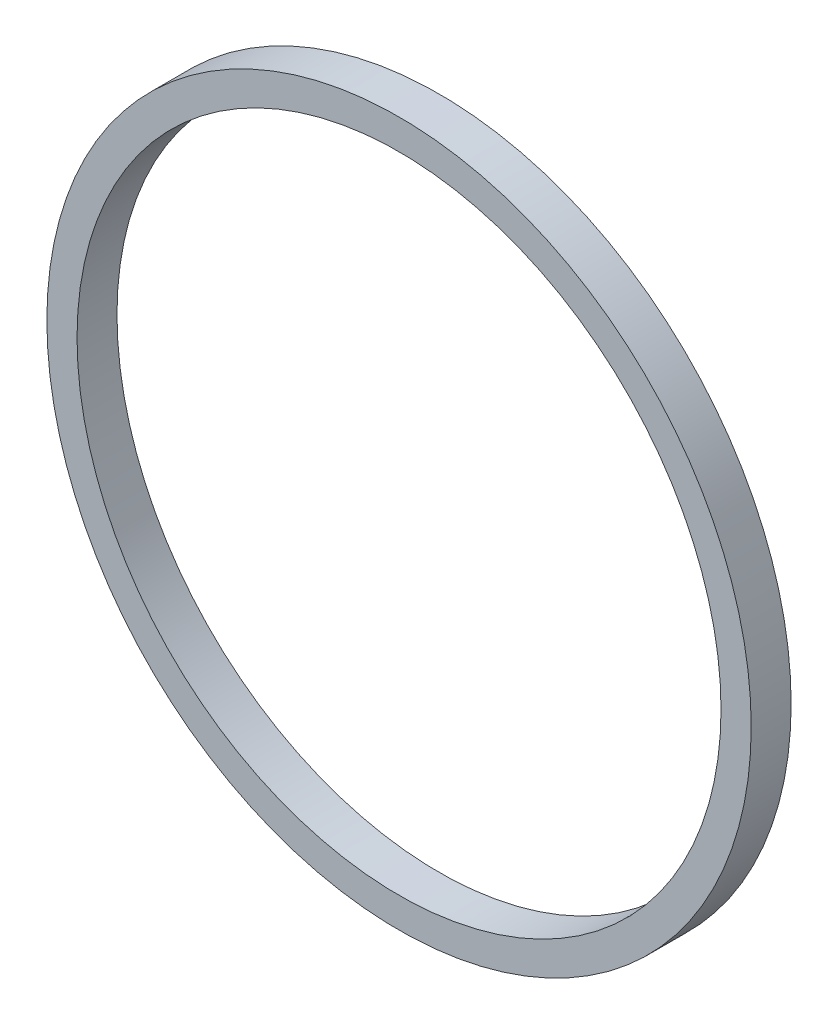
SolidWorks part; units mm, degrees
ref_plane "前基準面" through (0, 0, 0) normal (0, 0, 1) x (1, 0, 0)
ref_plane "上基準面" through (0, 0, 0) normal (0, 1, 0) x (1, 0, 0)
ref_plane "右基準面" through (0, 0, 0) normal (1, 0, 0) x (0, 0, -1)
sketch "Sketch1" plane through (0, 0, 0) normal (0, 0, 1) x (1, 0, 0)
  circle A9 centre (0, 0) radius 17.5
  circle A10 centre (0, 0) radius 16
extrude "Boss-Extrude1" add sketch "Sketch1" along normal blind 1.9844
